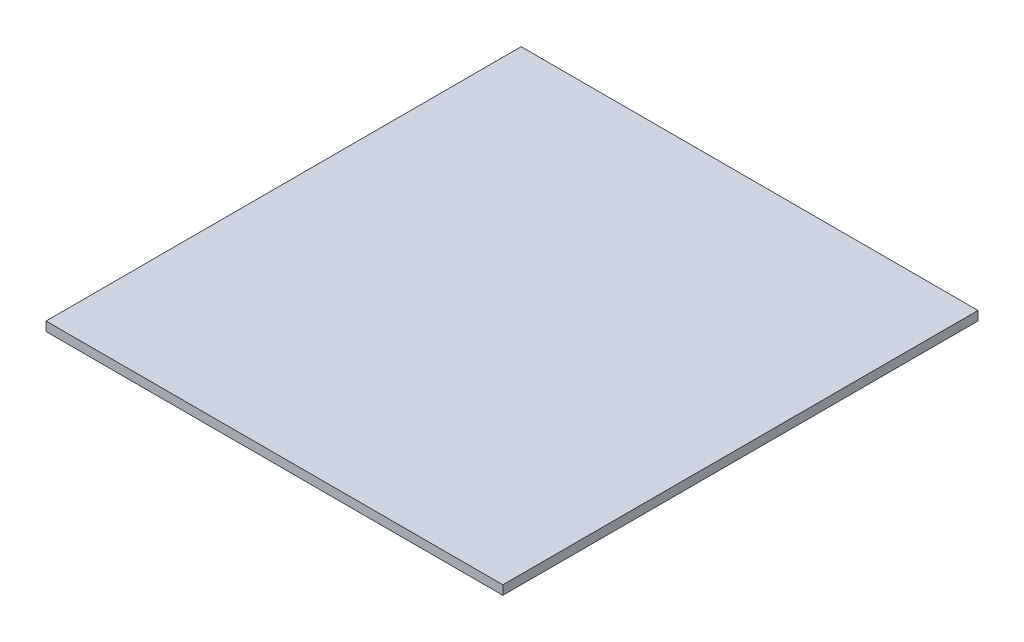
SolidWorks part; units mm, degrees
ref_plane "Front Plane" through (0, 0, 0) normal (0, 0, 1) x (1, 0, 0)
ref_plane "Top Plane" through (0, 0, 0) normal (0, 1, 0) x (1, 0, 0)
ref_plane "Right Plane" through (0, 0, 0) normal (1, 0, 0) x (0, 0, -1)
sketch "Sketch1" plane through (0, 0, 0) normal (0, 1, 0) x (1, 0, 0)
  line L1 (-100, -104) -> (100, -104)
  line L2 (-100, -104) -> (-100, 104)
  line L3 (-100, 104) -> (100, 104)
  line L4 (100, -104) -> (100, 104)
  line L5 (-100, -104) -> (100, 104) construction
  line L6 (-100, 104) -> (100, -104) construction
  point P0 (0, 0)
  dimension "D1" = 208
  dimension "D2" = 200
extrude "body" add sketch "Sketch1" along normal blind 4
